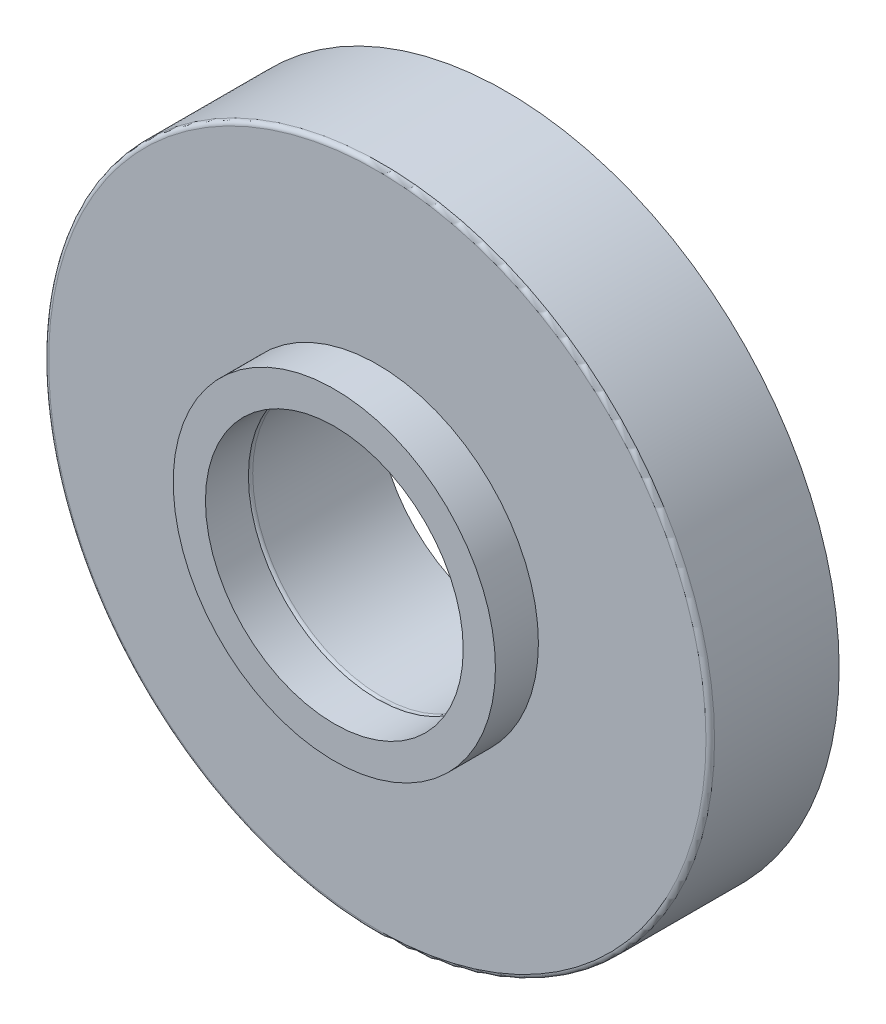
SolidWorks part; units mm, degrees
ref_plane "Спереди" through (0, 0, 0) normal (0, 0, 1) x (1, 0, 0)
ref_plane "Сверху" through (0, 0, 0) normal (0, 1, 0) x (1, 0, 0)
ref_plane "Справа" through (0, 0, 0) normal (1, 0, 0) x (0, 0, -1)
sketch "Эскиз1" plane through (0, 0, 0) normal (0, 0, 1) x (1, 0, 0)
  circle A0 centre (0, 0) radius 7.75
  dimension "D1" = 15.5
extrude "Бобышка-Вытянуть1" add sketch "Эскиз1" along normal blind 3
sketch "Эскиз2" plane through (0, 0, 3) normal (0, 0, 1) x (1, 0, 0)
  circle A0 centre (0, 0) radius 3.75
  dimension "D1" = 7.5
extrude "Бобышка-Вытянуть2" add sketch "Эскиз2" along normal blind 1 separate body
sketch "Эскиз3" plane through (0, 0, 4) normal (0, 0, 1) x (1, 0, 0)
  circle A0 centre (0, 0) radius 3
  dimension "D1" = 6
extrude "Вырез-Вытянуть1" cut sketch "Эскиз3" against normal through all
fillet "Скругление1" radius 0.1 2 edges at (7.75, 0, 3) (3, 0, 3)
